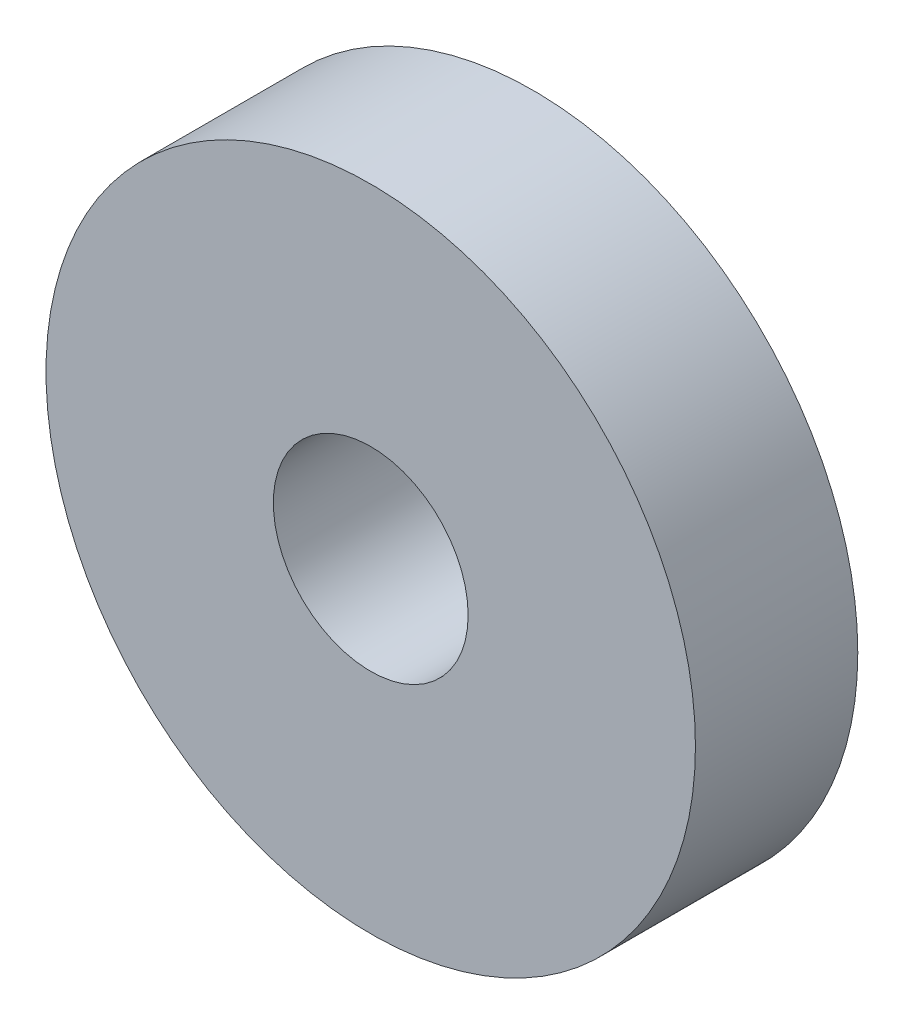
SolidWorks part; units mm, degrees
ref_plane "Plan de face" through (0, 0, 0) normal (0, 0, 1) x (1, 0, 0)
ref_plane "Plan de dessus" through (0, 0, 0) normal (0, 1, 0) x (1, 0, 0)
ref_plane "Plan de droite" through (0, 0, 0) normal (1, 0, 0) x (0, 0, -1)
sketch "Esquisse1" plane through (0, 0, 0) normal (0, 0, 1) x (1, 0, 0)
  circle A0 centre (0, 0) radius 10
  dimension "D1" = 20
extrude "Boss.-Extru.1" add sketch "Esquisse1" along normal blind 5
sketch "Esquisse2" plane through (0, 0, 5) normal (0, 0, 1) x (1, 0, 0)
  circle A0 centre (0, 0) radius 3
  dimension "D1" = 6
extrude "Enlèv. mat.-Extru.1" cut sketch "Esquisse2" against normal through all
